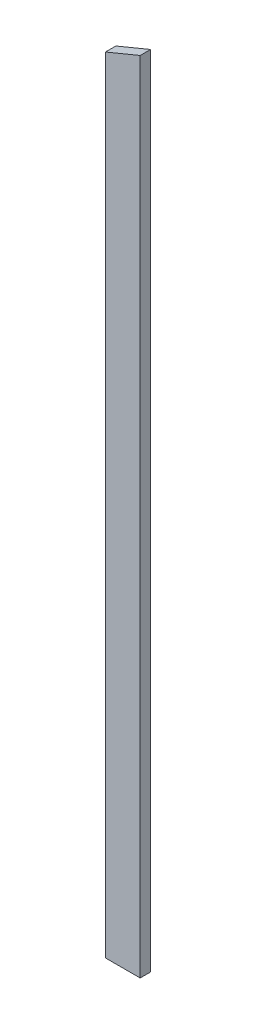
SolidWorks part; units mm, degrees
material "Pine"
ref_plane "Front Plane" through (0, 0, 0) normal (0, 0, 1) x (1, 0, 0)
ref_plane "Top Plane" through (0, 0, 0) normal (0, 1, 0) x (1, 0, 0)
ref_plane "Right Plane" through (0, 0, 0) normal (1, 0, 0) x (0, 0, -1)
sketch "Sketch1" plane through (0, 0, 0) normal (0, 0, 1) x (1, 0, 0)
  line L0 (-108.5345, -3.9032) -> (-108.5345, 1464.0363)
  line L1 (-108.5345, -3.9032) -> (-870.5345, -3.9032)
  line L2 (-870.5345, -3.9032) -> (-870.5345, 625.8363)
  line L3 (-972.1345, 737.9573) -> (-972.1345, 834.2968)
  line L4 (-768.9345, 834.2968) -> (-768.9345, 986.6968)
  line L5 (-972.1345, 834.2968) -> (-768.9345, 834.2968)
  line L6 (-528.0858, 1843.9468) -> (-737.1845, 1843.9468)
  line L7 (-968.4148, 728.977) -> (-874.2542, 634.8165)
  line L8 (-737.1845, 1672.0154) -> (-737.1845, 1762.6932)
  line L9 (-520.195, 1875.6968) -> (-756.2345, 1875.6968)
  line L10 (-112.2542, 1473.0165) -> (-511.2148, 1871.977)
  line L11 (-737.1845, 1692.941) -> (-241.631, 1467.6894)
  line L12 (-596.8655, 1608.234) -> (-737.1845, 983.1768)
  line L13 (-763.9746, 985.3593) -> (-203.7845, 834.2968)
  line L14 (-761.4898, 1669.1128) -> (-638.6318, 1613.2683)
  line L15 (-631.4955, 1598.9249) -> (-768.9345, 986.6968)
  line L16 (-768.9345, 1680.6745) -> (-768.9345, 1862.9968)
  line L17 (-737.1845, 1780.4468) -> (-737.1845, 1843.9468)
  line L18 (-737.1845, 1692.941) -> (-737.1845, 1843.9468) construction
  line L19 (-737.1845, 1692.941) -> (-737.1845, 1762.6932) construction
  line L20 (-838.7845, -3.9032) -> (-838.7845, 834.2968)
  line L21 (-745.0674, 1675.5986) -> (-249.5139, 1450.347) construction
  line L22 (-140.2845, -3.9032) -> (-140.2845, 1456.1455)
  line L23 (-140.2845, 1456.1455) -> (-528.0858, 1843.9468)
  line L24 (-537.8111, 1581.3911) -> (-673.6845, 976.1369)
  line L25 (-768.9345, 966.9663) -> (-203.7845, 814.5663)
  line L26 (-737.1845, 1672.0154) -> (-203.7845, 1429.5608)
  line L27 (-528.0858, 1843.9468) -> (-554.3883, 1780.4468)
  line L28 (-140.2845, 1456.1455) -> (-203.7845, 1429.8429)
  line L29 (-775.2845, -3.9032) -> (-775.2845, 834.2968)
  line L30 (-773.8944, 968.3038) -> (-208.7444, 815.9038) construction
  line L31 (-203.7845, -3.9032) -> (-203.7845, 1429.8429)
  line L32 (-203.7845, 1429.8429) -> (-554.3883, 1780.4468)
  line L33 (-554.3883, 1780.4468) -> (-737.1845, 1780.4468)
  line L34 (-768.9345, 966.9663) -> (-763.9746, 985.3593)
  line L35 (-737.1845, 1762.6932) -> (-369.5099, 1595.5683)
  line L36 (-673.6845, 1733.8295) -> (-599.2171, 1699.9807) construction
  line L37 (-737.1845, 1692.941) -> (-625.4936, 1642.1724) construction
  line L38 (-538.5586, 1578.0615) -> (-673.6845, 976.1369) construction
  line L39 (-600.5166, 1591.9704) -> (-737.1845, 983.1768) construction
  line L40 (-554.3883, 1780.4468) -> (-673.6845, 1780.4468) construction
  line L41 (-203.7845, 91.3468) -> (-203.7845, 1429.8429) construction
  line L42 (-140.2845, 27.8468) -> (-140.2845, 1456.1455) construction
  line L43 (-775.2845, 91.3468) -> (-775.2845, 625.8363) construction
  line L44 (-838.7845, 27.8468) -> (-838.7845, 625.8363) construction
  line L45 (-203.7845, 91.3468) -> (-775.2845, 91.3468) construction
  line L46 (-140.2845, 27.8468) -> (-838.7845, 27.8468) construction
  line L47 (-940.3845, 745.8481) -> (-851.8036, 657.2672) construction
  line L48 (-843.7807, 739.0468) -> (-806.9023, 702.1685) construction
  line L49 (-843.7807, 739.0468) -> (-673.6845, 739.0468) construction
  line L50 (-940.3845, 802.5468) -> (-737.1845, 802.5468) construction
  line L51 (-940.3845, 745.8481) -> (-940.3845, 802.5468) construction
  line L52 (-843.7807, 739.0468) -> (-843.7807, 739.0468) construction
  line L53 (-673.6845, 1733.8295) -> (-673.6845, 1780.4468) construction
  line L54 (-756.2345, 1692.941) -> (-756.2345, 1792.2779) construction
  line L55 (-756.2345, 1792.2779) -> (-361.627, 1612.9108) construction
  line L56 (-673.6845, 739.0468) -> (-673.6845, 976.1369) construction
  line L57 (-737.1845, 802.5468) -> (-737.1845, 983.1768) construction
  line L58 (-768.9345, 986.6968) -> (-203.7845, 834.2968) construction
  line L59 (-203.7845, 834.2968) -> (-208.7444, 815.9038)
  line L60 (-768.9345, 901.198) -> (-203.7845, 748.798)
  line L61 (-846.7775, 922.1894) -> (-163.9675, 738.0608) construction
  line L62 (-768.9345, 966.9663) -> (-208.7444, 815.9038) construction
  line L64 (-808.7515, 1063.2022) -> (-125.9415, 879.0737) construction
  line L65 (-125.9415, 879.0737) -> (-163.9675, 738.0608) construction
  line L66 (-846.7775, 922.1894) -> (-808.7515, 1063.2022) construction
  arc A0 (-108.5345, 1464.0363) -> (-112.2542, 1473.0165) centre (-121.2345, 1464.0363) ccw
  arc A1 (-511.2148, 1871.977) -> (-520.195, 1875.6968) centre (-520.195, 1862.9968) ccw
  arc A2 (-768.9345, 1862.9968) -> (-756.2345, 1875.6968) centre (-756.2345, 1862.9968) cw
  arc A3 (-768.9345, 1680.6745) -> (-761.4898, 1669.1128) centre (-756.2345, 1680.6745) ccw
  arc A4 (-631.4955, 1598.9249) -> (-638.6318, 1613.2683) centre (-643.8871, 1601.7067) ccw
  arc A5 (-972.1345, 737.9573) -> (-968.4148, 728.977) centre (-959.4345, 737.9573) ccw
  arc A6 (-870.5345, 625.8363) -> (-874.2542, 634.8165) centre (-883.2345, 625.8363) ccw
  arc A7 (-737.1845, 1843.9468) -> (-737.1845, 1843.9468) centre (-737.1845, 1843.9468) cw
  arc A8 (-737.1845, 1692.941) -> (-737.1845, 1692.941) centre (-737.1845, 1692.941) ccw
  arc A12 (-140.2845, 1456.1455) -> (-140.2845, 1456.1455) centre (-140.2845, 1456.1455) ccw
  arc A13 (-528.0858, 1843.9468) -> (-528.0858, 1843.9468) centre (-528.0858, 1843.9468) ccw
  arc A14 (-600.5166, 1591.9704) -> (-625.4936, 1642.1724) centre (-643.8871, 1601.7067) ccw construction
  arc A16 (-203.7845, 1429.8429) -> (-203.7845, 1429.8429) centre (-203.7845, 1429.8429) ccw
  arc A17 (-554.3883, 1780.4468) -> (-554.3883, 1780.4468) centre (-554.3883, 1780.4468) ccw
  arc A18 (-673.6845, 1780.4468) -> (-673.6845, 1780.4468) centre (-673.6845, 1780.4468) cw
  arc A19 (-673.6845, 1733.8295) -> (-673.6845, 1733.8295) centre (-673.6845, 1733.8295) ccw
  arc A20 (-838.7845, 625.8363) -> (-851.8036, 657.2672) centre (-883.2345, 625.8363) ccw construction
  arc A21 (-775.2845, 625.8363) -> (-806.9023, 702.1685) centre (-883.2345, 625.8363) ccw construction
  arc A22 (-843.7807, 739.0468) -> (-843.7807, 739.0468) centre (-843.7807, 739.0468) ccw construction
  arc A23 (-940.3845, 745.8481) -> (-940.3845, 745.8481) centre (-940.3845, 745.8481) ccw construction
  arc A24 (-756.2345, 1692.941) -> (-745.0674, 1675.5986) centre (-737.1845, 1692.941) ccw construction
  dimension "D1" = 12.7
  dimension "D2" = 31.75
  dimension "D3" = 63.5
  dimension "D4" = 19.05
  dimension "D5" = 19.05
  dimension "D6" = 63.5
sketch "Sketch2" plane through (0, 0, 0) normal (0, 0, 1) x (1, 0, 0)
  line L0 (-528.0858, 1843.9468) -> (-737.1845, 1843.9468)
  line L1 (-737.1845, 1780.4468) -> (-737.1845, 1843.9468)
  line L2 (-528.0858, 1843.9468) -> (-554.3883, 1780.4468)
  line L3 (-554.3883, 1780.4468) -> (-737.1845, 1780.4468)
sketch "Sketch3" plane through (0, 0, 0) normal (0, 0, 1) x (1, 0, 0)
  line L0 (-140.2845, 1456.1455) -> (-528.0858, 1843.9468)
  line L1 (-528.0858, 1843.9468) -> (-554.3883, 1780.4468)
  line L2 (-140.2845, 1456.1455) -> (-203.7845, 1429.8429)
  line L3 (-203.7845, 1429.8429) -> (-554.3883, 1780.4468)
sketch "Sketch4" plane through (0, 0, 0) normal (0, 0, 1) x (1, 0, 0)
  line L0 (-140.2845, -3.9032) -> (-203.7845, -3.9032)
  line L1 (-140.2845, -3.9032) -> (-140.2845, 1456.1455)
  line L2 (-140.2845, 1456.1455) -> (-203.7845, 1429.8429)
  line L3 (-203.7845, -3.9032) -> (-203.7845, 1429.8429)
sketch "Sketch5" plane through (0, 0, 0) normal (0, 0, 1) x (1, 0, 0)
  line L0 (-737.1845, 1672.0154) -> (-737.1845, 1762.6932)
  line L1 (-737.1845, 1692.941) -> (-241.631, 1467.6894)
  line L2 (-203.7845, 1429.8429) -> (-554.3883, 1780.4468)
  line L3 (-737.1845, 1762.6932) -> (-369.5099, 1595.5683)
sketch "Sketch6" plane through (0, 0, 0) normal (0, 0, 1) x (1, 0, 0)
  line L0 (-596.8655, 1608.234) -> (-737.1845, 983.1768)
  line L1 (-763.9746, 985.3593) -> (-203.7845, 834.2968)
  line L2 (-537.8111, 1581.3911) -> (-673.6845, 976.1369)
  line L3 (-737.1845, 1672.0154) -> (-203.7845, 1429.5608)
sketch "Sketch7" plane through (0, 0, 0) normal (0, 0, 1) x (1, 0, 0)
  line L0 (-768.9345, 834.2968) -> (-768.9345, 986.6968)
  line L1 (-768.9345, 966.9663) -> (-203.7845, 814.5663)
  line L2 (-203.7845, -3.9032) -> (-203.7845, 1429.8429)
  line L3 (-768.9345, 901.198) -> (-203.7845, 748.798)
extrude "Boss-Extrude1" add sketch "Sketch4" along normal blind 19.05
